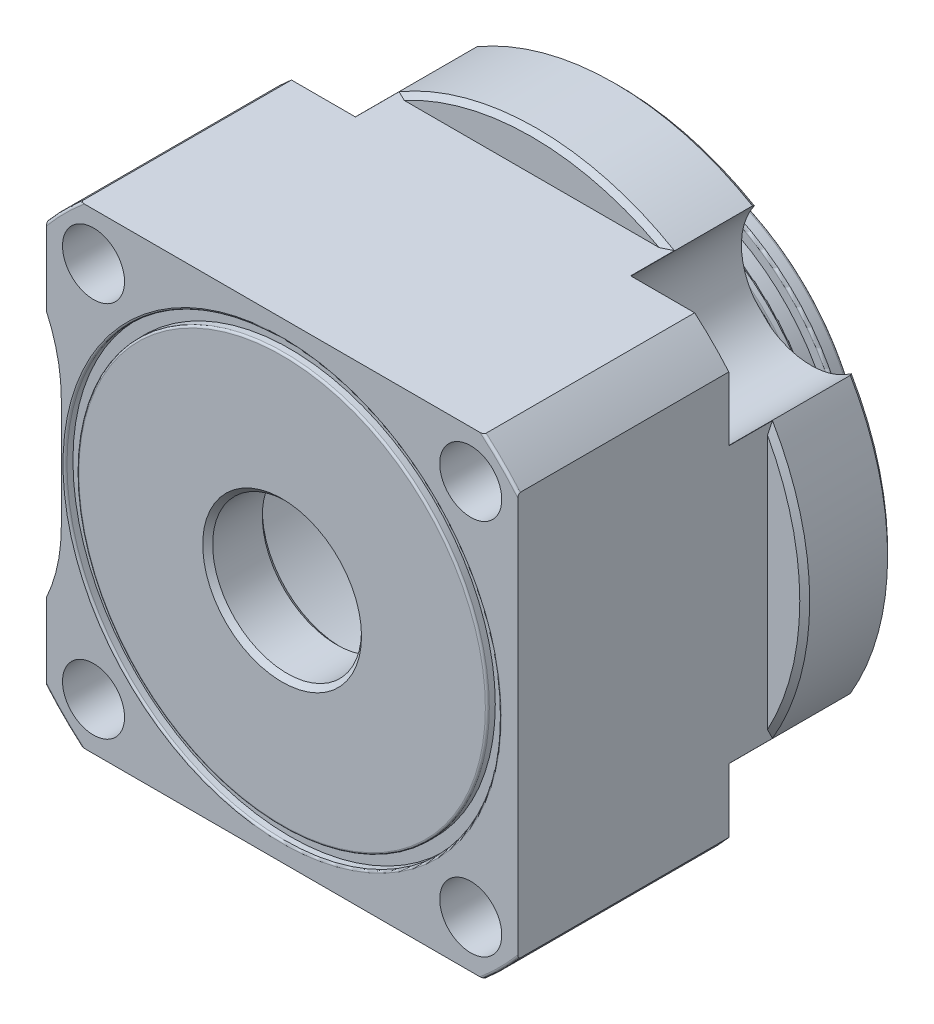
SolidWorks part; units mm, degrees
ref_plane "Front Plane" through (0, 0, 0) normal (0, 0, 1) x (1, 0, 0)
ref_plane "Top Plane" through (0, 0, 0) normal (0, 1, 0) x (1, 0, 0)
ref_plane "Right Plane" through (0, 0, 0) normal (1, 0, 0) x (0, 0, -1)
ref_plane "Rear Plane" through (0, 0, -77.5) normal (0, 0, -1) x (-1, 0, 0)
sketch "Sketch1" plane through (0, 0, 0) normal (1, 0, 0) x (0, 0, -1)
  line L0 (0, 0) -> (77.5, 0) construction
  line L1 (1, 15) -> (0, 16)
  line L2 (0, 16) -> (0, 40.95)
  line L3 (0.4, 41.35) -> (1.6, 41.35)
  line L4 (1.6, 41.35) -> (1.6, 43.75)
  line L5 (1.6, 43.75) -> (0.4, 43.75)
  line L6 (0, 44.15) -> (0, 62)
  line L7 (0.5, 62.5) -> (49.8, 62.5)
  line L8 (50.3, 62) -> (50.3, 55)
  line L9 (50.3, 55) -> (67, 55)
  line L10 (68, 54) -> (68, 41)
  line L11 (69, 40) -> (70, 40)
  line L12 (70.5, 39.5) -> (70.5, 37.65)
  line L13 (70.5, 37.65) -> (74.5, 37.65)
  line L14 (74.5, 37.65) -> (74.5, 39.5)
  line L15 (75, 40) -> (77, 40)
  line L17 (77.5, 39.5) -> (77.5, 36.025)
  line L18 (76.5, 35.025) -> (72.5, 35.025)
  line L19 (72.5, 35.025) -> (72.5, 33.525)
  line L20 (71.5, 32.525) -> (12, 32.525)
  line L21 (12, 32.525) -> (12, 16)
  line L22 (12, 16) -> (11, 15)
  line L23 (11, 15) -> (1, 15)
  line L24 (67, 55) -> (68, 54)
  arc A0 (72.5, 33.525) -> (71.5, 32.525) centre (71.5, 33.525) cw
  arc A1 (77.5, 36.025) -> (76.5, 35.025) centre (76.5, 36.025) cw
  arc A2 (68, 41) -> (69, 40) centre (69, 41) ccw
  arc A3 (0, 62) -> (0.5, 62.5) centre (0.5, 62) cw
  arc A4 (49.8, 62.5) -> (50.3, 62) centre (49.8, 62) cw
  arc A5 (70, 40) -> (70.5, 39.5) centre (70, 39.5) cw
  arc A6 (74.5, 39.5) -> (75, 40) centre (75, 39.5) cw
  arc A7 (77, 40) -> (77.5, 39.5) centre (77, 39.5) cw
  arc A8 (0, 40.95) -> (0.4, 41.35) centre (0.4, 40.95) cw
  arc A9 (0.4, 43.75) -> (0, 44.15) centre (0.4, 44.15) cw
  dimension "D27" = 1
  dimension "D7" = 0.5
  dimension "D28" = 0.4
  dimension "D1" = 77.5
  dimension "D3" = 45
  dimension "D4" = 45
  dimension "D5" = 1
  dimension "D6" = 1
  dimension "D8" = 1.6
  dimension "D9" = 50.3
  dimension "D10" = 9.5
  dimension "D11" = 7
  dimension "D12" = 4
  dimension "D13" = 5
  dimension "D14" = 60.5
  dimension "D15" = 12
  dimension "D16" = 15
  dimension "D17" = 41.35
  dimension "D18" = 43.75
  dimension "D19" = 62.5
  dimension "D20" = 32.525
  dimension "D21" = 35.025
  dimension "D22" = 37.65
  dimension "D23" = 40
  dimension "D24" = 55
  dimension "D25" = 1
  dimension "D26" = 45
revolve "Revolve1" add sketch "Sketch1" angle 360 about L0
sketch "Sketch2" plane through (0, 0, 0) normal (0, 0, 1) x (1, 0, 0)
  line L0 (63.4656, 0) -> (-63.4656, 0) construction
  line L1 (0, -60.7171) -> (0, 60.7171) construction
  line L2 (-47.5, 47.5) -> (-47.5, 25)
  line L3 (47.5, 47.5) -> (47.5, -47.5)
  line L4 (-47.5, 47.5) -> (47.5, 47.5)
  line L5 (-47.5, -47.5) -> (47.5, -47.5)
  line L7 (-47.5, 48.557) -> (-47.5, -47.5575) construction
  line L8 (47.5, 48.557) -> (47.5, -47.5575) construction
  line L11 (-47.5, -25) -> (-47.5, -47.5)
  line L13 (-44.5, 11.2523) -> (-44.5, -11.2523)
  line L15 (-44.5, 47.5) -> (-44.5, 0) construction
  line L16 (-47.5, 47.5) -> (-47.5, 0) construction
  arc A0 (-44.5, 11.2523) -> (-47.5, 25) centre (-77.5, 11.2523) ccw
  arc A4 (-44.5, -11.2523) -> (-47.5, -25) centre (-77.5, -11.2523) cw
  point P15 (47.5, 0)
  dimension "D6" = 33
  dimension "D7" = 3
  dimension "D2" = 47.5
  dimension "D3" = 95
  dimension "D5" = 47.5
  dimension "D8" = 25
  dimension "D9" = 50
extrude "Cut-Extrude2" cut sketch "Sketch2" against normal blind 50.3 flip side to cut
sketch "Sketch4" plane through (0, 0, 0) normal (0, 0, 1) x (1, 0, 0)
  line L0 (-47.5, -25) -> (-47.5, -47.5) construction
  line L1 (-44.5, 11.2523) -> (-44.5, -11.2523) construction
  line L2 (-47.5, 47.5) -> (-47.5, 25) construction
  line L3 (-47.5, -25) -> (-47.5, -47.5)
  line L4 (-44.5, 11.2523) -> (-44.5, -11.2523)
  line L5 (-47.5, 47.5) -> (-47.5, 25)
  line L6 (-47.5, 47.5) -> (-61.5053, 47.5)
  line L7 (-61.5053, 47.5) -> (-61.5053, -47.5)
  line L8 (-61.5053, -47.5) -> (-47.5, -47.5)
  arc A0 (-47.5, -25) -> (-44.5, -11.2523) centre (-77.5, -11.2523) ccw construction
  arc A1 (-44.5, 11.2523) -> (-47.5, 25) centre (-77.5, 11.2523) ccw construction
  arc A2 (-47.5, -25) -> (-44.5, -11.2523) centre (-77.5, -11.2523) ccw
  arc A3 (-44.5, 11.2523) -> (-47.5, 25) centre (-77.5, 11.2523) ccw
extrude "Cut-Extrude4" cut sketch "Sketch4" against normal through all
sketch "Sketch3" plane through (0, 0, -77.5) normal (0, 0, -1) x (-1, 0, 0)
  line L0 (0, 0) -> (0, 59.0013) construction
  line L1 (0, 0) -> (58.0485, 0) construction
  line L2 (0, 0) -> (-38.5373, 38.5373) construction
  line L3 (0, 0) -> (38.5373, -38.5373) construction
  line L4 (0, 0) -> (38.5373, 38.5373) construction
  line L5 (0, 0) -> (-38.5373, -38.5373) construction
  line L6 (28.2984, 28.9893) -> (44.502, 11.6131)
  line L7 (44.5, 11.2523) -> (44.5, -11.2523)
  line L8 (28.2984, -28.9893) -> (44.502, -11.6131)
  arc A0 (27.764, 47.478) -> (-27.764, 47.478) centre (0, 0) ccw
  arc A1 (27.764, 47.478) -> (28.2984, 28.9893) centre (38.5373, 38.5373) ccw
  arc A2 (27.764, -47.478) -> (28.2984, -28.9893) centre (38.5373, -38.5373) cw
  arc A3 (47.5, 25) -> (44.5, 11.2523) centre (77.5, 11.2523) ccw construction
  arc A4 (44.502, 11.6131) -> (44.5, 11.2523) centre (77.5, 11.2523) ccw
  arc A5 (-27.764, -47.478) -> (27.764, -47.478) centre (0, 0) ccw
  arc A6 (44.502, -11.6131) -> (44.5, -11.2523) centre (77.5, -11.2523) cw
  arc A7 (-27.764, -47.478) -> (-47.478, -27.764) centre (-38.5373, -38.5373) ccw
  arc A8 (-47.478, -27.764) -> (-47.478, 27.764) centre (0, 0) cw
  arc A9 (-27.764, 47.478) -> (-47.478, 27.764) centre (-38.5373, 38.5373) cw
  dimension "D1" = 110
  dimension "D2" = 14
  dimension "D3" = 45
  dimension "D4" = 40.5
  dimension "D5" = 47
extrude "Cut-Extrude3" cut sketch "Sketch3" against normal blind 35 flip side to cut
hole_wizard "Ø12.5 (12.5) Diameter Hole1" positions "Sketch5" profile "Sketch6" hole size "Ø12.5" standard "ANSI Metric" end condition through all
sketch "Sketch5" plane through (0, 0, 0) normal (0, 0, 1) x (1, 0, 0)
  point P0 (-38, 38)
  point P2 (38, 38)
  point P4 (38, -38)
  point P6 (-38, -38)
  dimension "D1" = 38
  dimension "D2" = 38
  dimension "D3" = 38
  dimension "D4" = 38
sketch "Sketch6" plane through (-38, 38, 0) normal (1, 0, 0) x (0, -1, 0)
  line L0 (0, 0) -> (0, 77.5)
  line L1 (0, 77.5) -> (6.25, 77.5)
  line L2 (6.25, 77.5) -> (6.25, 0)
  line L5 (6.25, 0) -> (0, 0)
  line L11 (0, -6.35) -> (0, 107.95) construction
  dimension "Thru Hole Dia." = 12.5
  dimension "Thru Hole Depth" = 77.5
sketch "Sketch8" plane through (0, 0, 0) normal (0, 1, 0) x (1, 0, 0)
  line L0 (0, 0) -> (0, 77.5) construction
  line L1 (-5.5, 77.5) -> (5.5, 77.5)
  line L2 (-2.6716, 75.5) -> (2.6716, 75.5)
  arc A0 (2.6716, 75.5) -> (5.5, 77.5) centre (2.6716, 78.5) ccw
  arc A1 (-2.6716, 75.5) -> (-5.5, 77.5) centre (-2.6716, 78.5) cw
  point P5 (0, 75.5)
  dimension "D3" = 3
  dimension "D1" = 77.5
  dimension "D2" = 2
  dimension "D4" = 5.5
  dimension "D5" = 11
extrude "Cut-Extrude5" cut sketch "Sketch8" against normal blind 42.5
chamfer "Chamfer1" distance 1 angle 45 3 edges at (0, -55, -50.3) (55, 0, -50.3) (0, 55, -50.3)
